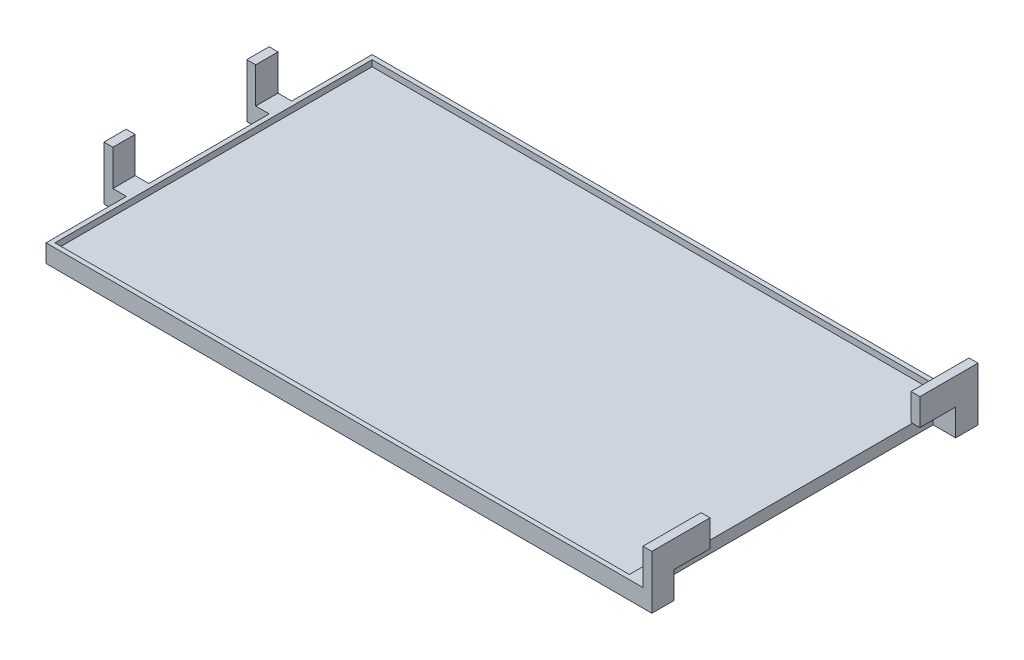
SolidWorks part; units mm, degrees
ref_plane "Plan de face" through (0, 0, 0) normal (0, 0, 1) x (1, 0, 0)
ref_plane "Plan de dessus" through (0, 0, 0) normal (0, 1, 0) x (1, 0, 0)
ref_plane "Plan de droite" through (0, 0, 0) normal (1, 0, 0) x (0, 0, -1)
sketch "Esquisse1" plane through (0, 0, 0) normal (0, 1, 0) x (1, 0, 0)
  line L1 (0, 0) -> (130.51, 0)
  line L2 (0, 0) -> (0, 72.96)
  line L3 (0, 72.96) -> (130.51, 72.96)
  line L4 (130.51, 0) -> (130.51, 72.96)
  dimension "D1" = 72.96
  dimension "D2" = 130.51
extrude "Boss.-Extru.4" add sketch "Esquisse1" along normal blind 4
sketch "Esquisse5" plane through (0, 4, 0) normal (0, 1, 0) x (1, 0, 0)
  line L8 (1, 71.96) -> (1, 1)
  line L9 (1, 1) -> (129.51, 1)
  line L10 (129.51, 1) -> (129.51, 71.96)
  line L11 (129.51, 71.96) -> (1, 71.96)
  line L12 (1, 71.96) -> (1, 1)
  line L13 (1, 1) -> (129.51, 1)
  line L14 (129.51, 1) -> (129.51, 71.96)
  line L15 (129.51, 71.96) -> (1, 71.96)
  dimension "D1" = 1
extrude "Enlèv. mat.-Extru.1" cut sketch "Esquisse5" against normal blind 1.36
sketch "Esquisse6" plane through (129.51, 0, 0) normal (-1, 0, 0) x (0, 0, 1)
  line L0 (-1, 4) -> (-71.96, 4) construction
  line L1 (-66.96, 4) -> (-6, 4)
  line L2 (-66.96, 4) -> (-66.96, 2.64)
  line L3 (-66.96, 2.64) -> (-6, 2.64)
  line L4 (-6, 4) -> (-6, 2.64)
  line L5 (-1, 2.64) -> (-71.96, 2.64) construction
  line L6 (-71.96, 2.64) -> (-71.96, 4) construction
  line L7 (-1, 2.64) -> (-1, 4) construction
  point P10 (-71.96, 3.32)
  dimension "D1" = 5
  dimension "D2" = 5
extrude "Enlèv. mat.-Extru.2" cut sketch "Esquisse6" against normal through all
ref_plane "Plan1" through (130.51, 0, 0) normal (1, 0, 0) x (0, 0, -1)
sketch "Esquisse12" plane through (0, 0, 0) normal (0, -1, 0) x (1, 0, 0)
  line L1 (130.51, -72.96) -> (135.555, -72.96)
  line L2 (130.51, -72.96) -> (130.51, -67.96)
  line L3 (130.51, -67.96) -> (135.555, -67.96)
  line L4 (135.555, -72.96) -> (135.555, -67.96)
  line L5 (130.51, 0) -> (135.555, 0)
  line L6 (130.51, 0) -> (130.51, -5)
  line L7 (130.51, -5) -> (135.555, -5)
  line L8 (135.555, 0) -> (135.555, -5)
  dimension "D1" = 5.045
  dimension "D2" = 5
  dimension "D3" = 5
  dimension "D4" = 5.045
extrude "Boss.-Extru.10" add sketch "Esquisse12" against normal blind 4
sketch "Esquisse14" plane through (0, 4, 0) normal (0, 1, 0) x (1, 0, 0)
  line L0 (135.555, 67.96) -> (130.51, 67.96) construction
  line L5 (135.555, 72.96) -> (133.555, 72.96)
  line L6 (135.555, 72.96) -> (135.555, 67.96)
  line L7 (135.555, 67.96) -> (133.555, 67.96)
  line L8 (133.555, 72.96) -> (133.555, 67.96)
  line L9 (0, 0) -> (135.555, 0) construction
  line L10 (135.555, 5) -> (133.555, 5)
  line L11 (135.555, 5) -> (135.555, 0)
  line L12 (135.555, 0) -> (133.555, 0)
  line L13 (133.555, 5) -> (133.555, 0)
  dimension "D1" = 2
extrude "Boss.-Extru.11" add sketch "Esquisse14" along normal blind 8
sketch "Esquisse15" plane through (0, 0, -5) normal (0, 0, -1) x (-1, 0, 0)
  line L0 (-133.555, 12) -> (-133.555, 4) construction
  line L1 (-135.555, 12) -> (-133.555, 12)
  line L2 (-135.555, 12) -> (-135.555, 6)
  line L3 (-135.555, 6) -> (-133.555, 6)
  line L4 (-133.555, 12) -> (-133.555, 6)
extrude "Boss.-Extru.12" add sketch "Esquisse15" along normal blind 8
sketch "Esquisse16" plane through (0, 0, -67.96) normal (0, 0, 1) x (1, 0, 0)
  line L0 (135.555, 12) -> (135.555, 0) construction
  line L1 (133.555, 12) -> (135.555, 12)
  line L2 (133.555, 12) -> (133.555, 6)
  line L3 (133.555, 6) -> (135.555, 6)
  line L4 (135.555, 12) -> (135.555, 6)
extrude "Boss.-Extru.13" add sketch "Esquisse16" along normal blind 8
sketch "Esquisse17" plane through (0, 0, 0) normal (0, -1, 0) x (1, 0, 0)
  line L0 (0, -72.96) -> (0, 0) construction
  line L1 (0, -54.96) -> (-5.045, -54.96)
  line L2 (0, -54.96) -> (0, -49.96)
  line L3 (0, -49.96) -> (-5.045, -49.96)
  line L4 (-5.045, -54.96) -> (-5.045, -49.96)
  line L6 (0, -23) -> (-5.045, -23)
  line L7 (0, -23) -> (0, -18)
  line L8 (0, -18) -> (-5.045, -18)
  line L9 (-5.045, -23) -> (-5.045, -18)
  dimension "D1" = 18
  dimension "D2" = 18
  dimension "D3" = 5
  dimension "D4" = 5
  dimension "D5" = 5.045
  dimension "D6" = 5.045
extrude "Boss.-Extru.14" add sketch "Esquisse17" against normal blind 4
sketch "Esquisse19" plane through (0, 4, 0) normal (0, 1, 0) x (1, 0, 0)
  line L0 (-5.045, 54.96) -> (0, 54.96) construction
  line L1 (-5.045, 49.96) -> (-3.045, 49.96)
  line L2 (-5.045, 49.96) -> (-5.045, 54.96)
  line L3 (-5.045, 54.96) -> (-3.045, 54.96)
  line L4 (-3.045, 49.96) -> (-3.045, 54.96)
  line L5 (-5.045, 23) -> (0, 23) construction
  line L6 (-5.045, 18) -> (-3.045, 18)
  line L7 (-5.045, 18) -> (-5.045, 23)
  line L8 (-5.045, 23) -> (-3.045, 23)
  line L9 (-3.045, 18) -> (-3.045, 23)
  dimension "D1" = 2
  dimension "D2" = 2
extrude "Boss.-Extru.15" add sketch "Esquisse19" along normal blind 8
